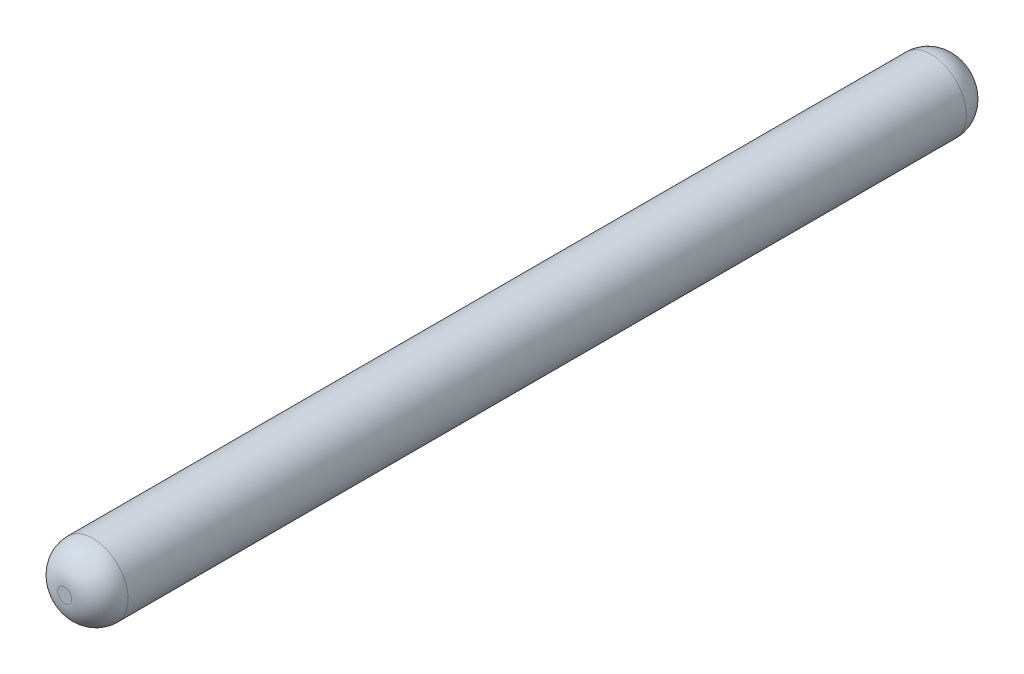
SolidWorks part; units mm, degrees
ref_plane "Alzado" through (0, 0, 0) normal (0, 0, 1) x (1, 0, 0)
ref_plane "Planta" through (0, 0, 0) normal (0, 1, 0) x (1, 0, 0)
ref_plane "Vista lateral" through (0, 0, 0) normal (1, 0, 0) x (0, 0, -1)
sketch "Croquis1" plane through (0, 0, 0) normal (0, 0, 1) x (1, 0, 0)
  circle A0 centre (0, 0) radius 0.5
extrude "Saliente-Extruir1" add sketch "Croquis1" along normal blind 12.7
fillet "Redondeo6" radius 0.4 2 edges at (0.5, 0, 0) (0.5, 0, 12.7)
